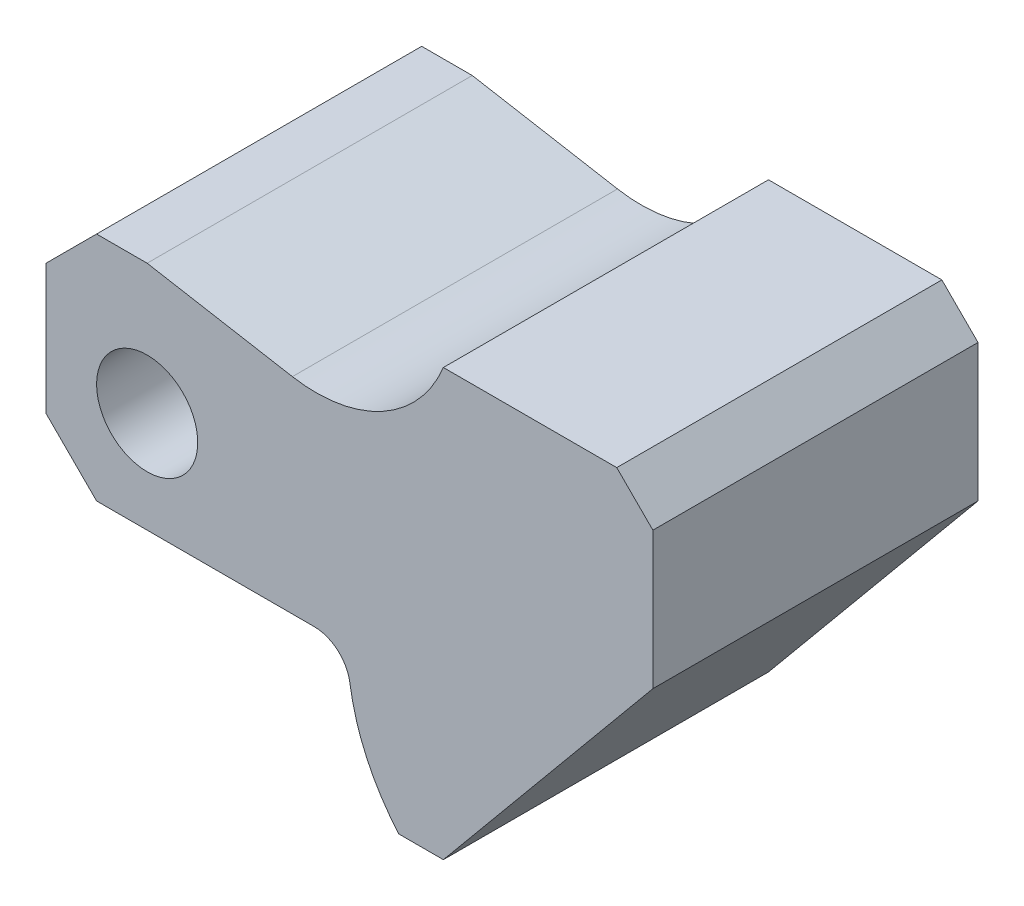
SolidWorks part; units mm, degrees
material "AISI 1020"
ref_plane "Plan de face" through (0, 0, 0) normal (0, 0, 1) x (1, 0, 0)
ref_plane "Plan de dessus" through (0, 0, 0) normal (0, 1, 0) x (1, 0, 0)
ref_plane "Plan de droite" through (0, 0, 0) normal (1, 0, 0) x (0, 0, -1)
sketch "Esquisse1" plane through (0, 0, 0) normal (0, 0, 1) x (1, 0, 0)
  line L0 (-14, 18) -> (0, 18)
  line L1 (70, -33) -> (-14, -33) construction
  line L2 (70, -33) -> (70, 26) construction
  line L3 (70, 26) -> (-14, 26) construction
  line L4 (-14, -33) -> (-14, 26) construction
  line L5 (0, 18) -> (20.104, 14.4551)
  line L6 (41, 26) -> (65, 26)
  line L7 (65, 26) -> (70, 26)
  line L8 (70, 26) -> (70, 2)
  line L9 (70, 2) -> (41, -33)
  line L10 (41, -33) -> (34.834, -33)
  line L12 (23.1125, -14) -> (-14, -14)
  line L13 (-14, -14) -> (-14, 18)
  circle A0 centre (0, 0) radius 7
  arc A1 (20.104, 14.4551) -> (41, 26) centre (23.4034, 33.1665) ccw
  arc A2 (34.834, -33) -> (28.0582, -18.2647) centre (56.7429, -14) cw
  arc A3 (28.0582, -18.2647) -> (23.1125, -14) centre (23.1125, -19) ccw
  point P18 (32.4447, -33)
  point P22 (32.7442, -33)
  point P23 (37.9623, -4)
  point P25 (67, 23.367)
  dimension "D13" = 5
  dimension "D14" = 29
  dimension "D9" = 19
  dimension "D18" = 14
  dimension "D1" = 84
  dimension "D2" = 59
  dimension "D4" = 24
  dimension "D5" = 14
  dimension "D6" = 14
  dimension "D7" = 32
  dimension "D8" = 19
  dimension "D12" = 10
  dimension "D15" = 29
  dimension "D16" = 14
  dimension "D17" = 19
  dimension "D3" = 29
extrude "Boss.-Extru.1" add sketch "Esquisse1" along normal blind 45
chamfer "Chanfrein1" distance 7 angle 45 2 edges at (-14, -14, 22.5) (-14, 18, 22.5)
chamfer "Chanfrein2" distance 5 angle 45 1 edges at (70, 26, 22.5)
equation "\"A\" = 84"
equation "\"B\" = 59"
equation "\"C\"= 45"
equation "\"D1@Boss.-Extru.1\"=\"C\""
equation "\"D1@Esquisse1\"=\"A\""
equation "\"D2@Esquisse1\"=\"B\""
